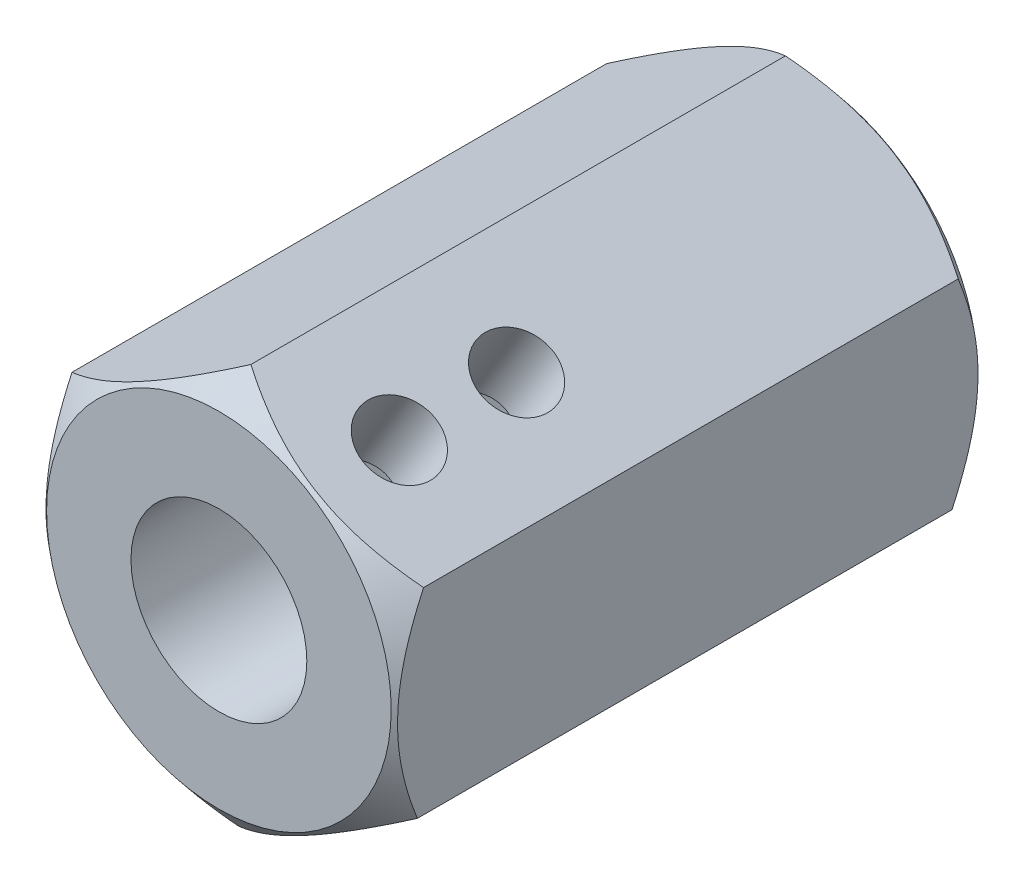
SolidWorks part; units mm, degrees
ref_plane "Front Plane" through (0, 0, 0) normal (0, 0, 1) x (1, 0, 0)
ref_plane "Top Plane" through (0, 0, 0) normal (0, 1, 0) x (1, 0, 0)
ref_plane "Right Plane" through (0, 0, 0) normal (1, 0, 0) x (0, 0, -1)
sketch "Sketch1" plane through (0, 0, 0) normal (0, 0, 1) x (1, 0, 0)
  line L1 (-6.1024, -3.2804) -> (-0.2103, -6.925)
  line L2 (-0.2103, -6.925) -> (5.8921, -3.6446)
  line L3 (5.8921, -3.6446) -> (6.1024, 3.2804)
  line L4 (6.1024, 3.2804) -> (0.2103, 6.925)
  line L5 (0.2103, 6.925) -> (-5.8921, 3.6446)
  line L6 (-5.8921, 3.6446) -> (-6.1024, -3.2804)
  circle A0 centre (0, 0) radius 6 construction
  dimension "D1" = 12
extrude "Boss-Extrude1" add sketch "Sketch1" along normal blind 20
sketch "Sketch2" plane through (0, 0, 0) normal (0, 0, -1) x (-1, 0, 0)
  circle A0 centre (0, 0) radius 2
  dimension "D1" = 4
extrude "Cut-Extrude1" cut sketch "Sketch2" against normal blind 20
sketch "Sketch3" plane through (0, 0, 20) normal (0, 0, 1) x (1, 0, 0)
  circle A0 centre (0, 0) radius 3
extrude "Cut-Extrude2" cut sketch "Sketch3" against normal blind 13.5
sketch "Sketch4" plane through (0, 0, 20) normal (0, 0, 1) x (1, 0, 0)
  circle A0 centre (0, 0) radius 5.8785
extrude "Cut-Extrude3" cut sketch "Sketch4" against normal through all draft 50 flip side to cut
ref_plane "Plane1" through (0, 0, 10) normal (0, 0, 1) x (1, 0, 0)
mirror "Mirror1" about plane through (0, 0, 10) normal (0, 0, 1) of "Cut-Extrude3"
sketch "Sketch5" plane through (3.1563, 5.1027, 0) normal (0.5261, 0.8504, 0) x (0.8504, -0.5261, 0)
  line L0 (-5.8785, -20) -> (5.8785, -20) construction
  line L1 (0, -20) -> (0, -10.707) construction
  circle A0 centre (0, -17) radius 1.25
  circle A1 centre (0, -13) radius 1.25
  dimension "D3" = 2.5
  dimension "D4" = 2.5
  dimension "D1" = 3
  dimension "D2" = 7
extrude "Cut-Extrude4" cut sketch "Sketch5" against normal up to next
